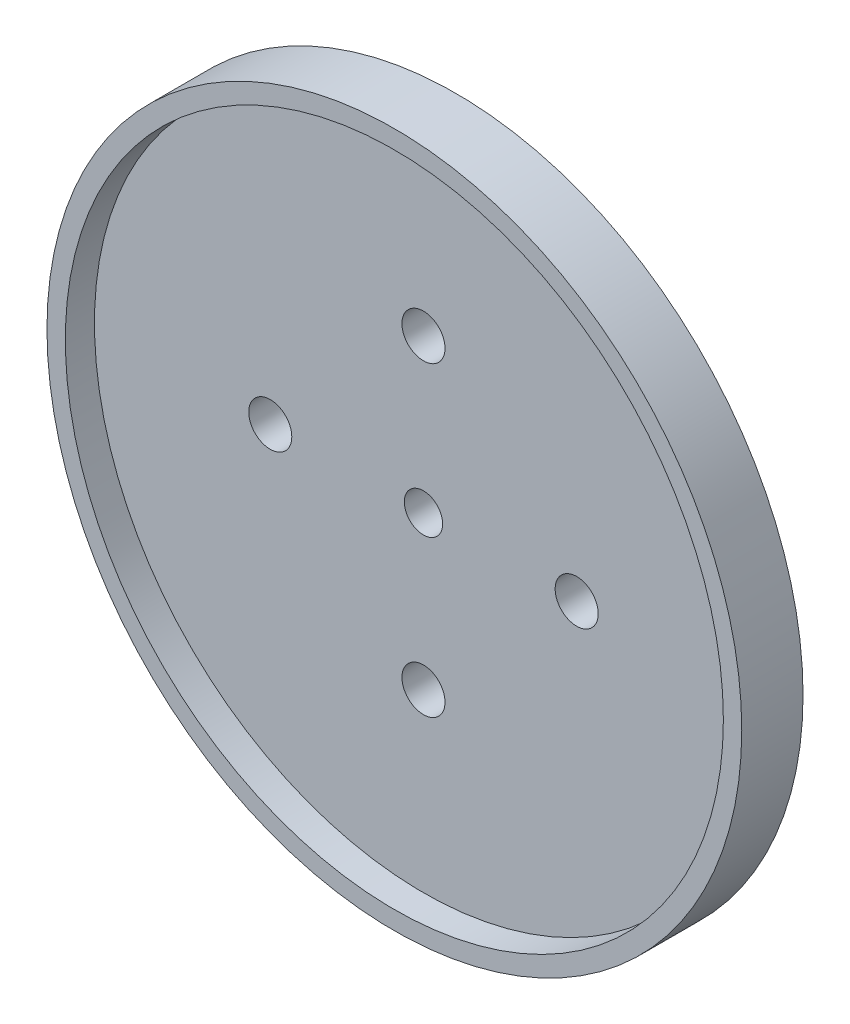
SolidWorks part; units mm, degrees
ref_plane "Front Plane" through (0, 0, 0) normal (0, 0, 1) x (1, 0, 0)
ref_plane "Top Plane" through (0, 0, 0) normal (0, 1, 0) x (1, 0, 0)
ref_plane "Right Plane" through (0, 0, 0) normal (1, 0, 0) x (0, 0, -1)
sketch "Sketch1" plane through (0, 0, 0) normal (0, 0, 1) x (1, 0, 0)
  circle A0 centre (0, 0) radius 57.5945
  dimension "D1" = 115.189
extrude "Extrude1" add sketch "Sketch1" along normal blind 10.16
sketch "Sketch2" plane through (0, 0, 10.16) normal (0, 0, 1) x (1, 0, 0)
  circle A0 centre (0, 0) radius 54.5465
  dimension "D1" = 109.093
extrude "Extrude2" cut sketch "Sketch2" against normal blind 4.826
hole_wizard "1/4 (0.25) Diameter Hole1" positions "Sketch4" profile "Sketch3" hole size "1/4" standard "Ansi Inch"
sketch "Sketch4" plane through (0, 0, 5.334) normal (0, 0, 1) x (1, 0, 0)
  point P1 (0, 0)
sketch "Sketch3" plane through (0, 0, 5.334) normal (1, 0, 0) x (0, -1, 0)
  line L0 (0, 0) -> (0, 8.2577)
  line L1 (0, 8.2577) -> (3.175, 6.35)
  line L2 (3.175, 6.35) -> (3.175, 0)
  line L5 (3.175, 0) -> (0, 0)
  line L10 (0, 8.2577) -> (-3.175, 6.35) construction
  line L11 (0, -6.35) -> (0, 107.95) construction
  dimension "Hole Dia." = 6.35
  dimension "Hole Depth" = 6.35
  dimension "Drill Angle" = 118
sketch "Sketch5" plane through (0, 0, 5.334) normal (0, 0, 1) x (1, 0, 0)
  line L0 (0, 0) -> (25.4, 0) construction
  dimension "D1" = 25.4
hole_wizard "1/4 Clearance Hole1" positions "3DSketch1" profile "Sketch6" hole size "1/4" standard "Ansi Inch" end condition through all
sketch3d "3DSketch1"
  point P0 (25.4, 0, 5.334)
sketch "Sketch6" plane through (25.4, 0, 5.334) normal (1, 0, 0) x (0, -1, 0)
  line L0 (0, 0) -> (0, 5.334)
  line L1 (0, 5.334) -> (3.5712, 5.334)
  line L2 (3.5712, 5.334) -> (3.5712, 0)
  line L5 (3.5712, 0) -> (0, 0)
  line L11 (0, -6.35) -> (0, 107.95) construction
  dimension "Thru Hole Dia." = 7.1425
  dimension "Thru Hole Depth" = 5.334
pattern_circular "CirPattern1" count 4 over 360 about axis through (0, 0, 0) along (0, 0, 1) of "1/4 Clearance Hole1"
